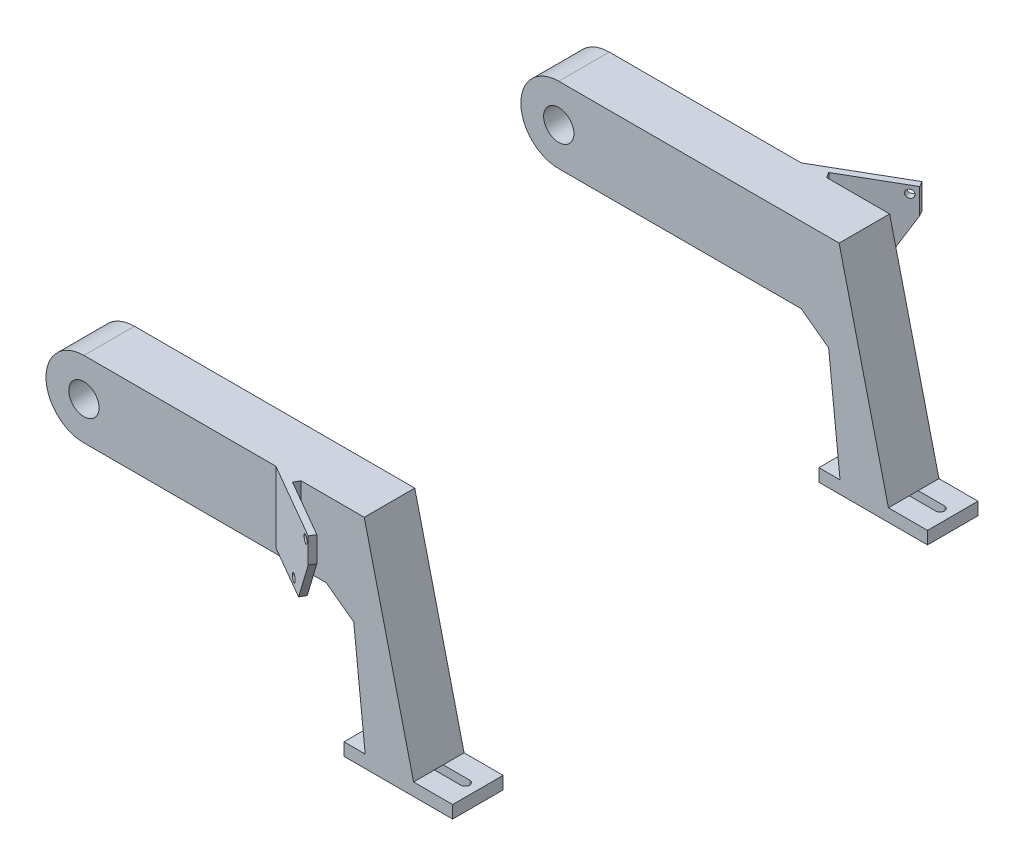
SolidWorks part; units mm, degrees
ref_plane "前视基准面" through (0, 0, 0) normal (0, 0, 1) x (1, 0, 0)
ref_plane "上视基准面" through (0, 0, 0) normal (0, 1, 0) x (1, 0, 0)
ref_plane "右视基准面" through (0, 0, 0) normal (1, 0, 0) x (0, 0, -1)
other "Configuration Table"
sketch "草图1" plane through (0, 0, 0) normal (0, 0, 1) x (1, 0, 0)
  line L1 (3.3481, 16.2319) -> (9.234, -39.7681)
  line L2 (9.234, -39.7681) -> (29.0728, -39.7681)
  line L3 (29.0728, -39.7681) -> (8.3481, 46.2319)
  line L4 (8.3481, 46.2319) -> (-102.6519, 46.2319)
  line L5 (3.3481, 16.2319) -> (-102.6519, 16.2319)
  line L8 (-112.6519, 46.2319) -> (-92.6519, 46.2319) construction
  arc A5 (-102.6519, 46.2319) -> (-102.6519, 16.2319) centre (-102.6519, 31.2319) ccw
  point P7 (-102.6519, 31.2319)
  dimension "D4" = 96
  dimension "D5" = 56
extrude "凸台-拉伸1" add sketch "草图1" along normal blind 20
sketch "草图9" plane through (0, 0, 20) normal (0, 0, 1) x (1, 0, 0)
  circle A0 centre (-102.6519, 31.2319) radius 6
extrude "切除-拉伸5" cut sketch "草图9" against normal through all
sketch "草图15" plane through (0, 0, 20) normal (0, 0, 1) x (1, 0, 0)
  line L0 (4.189, 8.2319) -> (-6.6519, 16.2319)
  line L1 (3.3481, 16.2319) -> (9.234, -39.7681) construction
  line L2 (-102.6519, 16.2319) -> (3.3481, 16.2319) construction
  line L3 (-6.6519, 16.2319) -> (3.3481, 16.2319)
  line L4 (3.3481, 16.2319) -> (4.189, 8.2319)
  dimension "D1" = 10
  dimension "D2" = 8
extrude "凸台-拉伸4" add sketch "草图15" against normal through all
sketch "草图16" plane through (0, 0, 20) normal (0, 0, 1) x (1, 0, 0)
  line L0 (0.3302, -34.7681) -> (0.3302, -49.7681) construction
  line L1 (0.3302, -39.7681) -> (43.3302, -39.7681)
  line L2 (0.3302, -39.7681) -> (0.3302, -34.7681)
  line L3 (0.3302, -34.7681) -> (43.3302, -34.7681)
  line L4 (43.3302, -39.7681) -> (43.3302, -34.7681)
  line L6 (9.234, -39.7681) -> (29.0728, -39.7681) construction
  dimension "D1" = 5
extrude "凸台-拉伸5" add sketch "草图16" against normal through all
sketch "草图17" plane through (0, -34.7681, 0) normal (0, 1, 0) x (1, 0, 0)
  line L0 (4.3302, -10) -> (38.3302, -10) construction
  line L1 (4.3302, -8.25) -> (38.3302, -8.25)
  line L2 (4.3302, -11.75) -> (38.3302, -11.75)
  line L3 (0.3302, -20.5) -> (43.3302, -20.5) construction
  line L6 (43.3302, 0) -> (43.3302, -20) construction
  arc A0 (4.3302, -8.25) -> (4.3302, -11.75) centre (4.3302, -10) ccw
  arc A1 (38.3302, -11.75) -> (38.3302, -8.25) centre (38.3302, -10) ccw
  point P2 (21.3302, -10)
  dimension "D1" = 10.5
  dimension "D2" = 3.5
  dimension "D4" = 5
extrude "切除-拉伸7" cut sketch "草图17" against normal through all
sketch "草图23" plane through (0, 46.2319, 0) normal (0, 1, 0) x (1, 0, 0)
  line L0 (-26.6519, -20) -> (3.659, -37.5)
  line L1 (8.3481, -20) -> (-102.6519, -20) construction
  line L2 (3.659, -37.5) -> (4.909, -35.3349)
  line L3 (4.909, -35.3349) -> (-21.6519, -20)
  line L4 (-21.6519, -20) -> (-26.6519, -20)
  dimension "D1" = 30
  dimension "D2" = 5
  dimension "D3" = 35
  dimension "D4" = 30
extrude "凸台-拉伸6" add sketch "草图23" along direction (0, 1, 0) on the side against the normal up to surface (30 mm away)
sketch "草图25" plane through (0, 46.2319, 0) normal (0, 1, 0) x (1, 0, 0)
  line L0 (-21.6519, -20) -> (-16.6519, -20)
  line L1 (8.3481, -20) -> (-21.6519, -20) construction
  line L2 (-16.6519, -20) -> (-17.9019, -22.1651)
  line L3 (4.909, -35.3349) -> (-21.6519, -20) construction
  line L4 (-17.9019, -22.1651) -> (-21.6519, -20)
  dimension "D1" = 5
extrude "凸台-拉伸7" add sketch "草图25" along direction (0, 1, 0) on the side against the normal up to surface (30 mm away)
sketch "草图26" plane through (-15.3232, 0, 26.5406) normal (-0.5, 0, 0.866) x (0.866, 0, 0.5)
  line L1 (21.9188, 16.2319) -> (-13.0812, 16.2319) construction
  circle A0 centre (19.0303, 43.2289) radius 1.55
  circle A1 centre (6.3303, 21.2319) radius 1.55
  dimension "D4" = 3.1
  dimension "D5" = 3.1
  dimension "D2" = 25.4
  dimension "D3" = 5
extrude "切除-拉伸8" cut sketch "草图26" against normal blind 10
sketch "草图27" plane through (-15.3232, 0, 26.5406) normal (-0.5, 0, 0.866) x (0.866, 0, 0.5)
  line L0 (21.9188, 36.2319) -> (10.3718, 16.2319)
  line L1 (21.9188, 16.2319) -> (21.9188, 46.2319) construction
  line L2 (21.9188, 16.2319) -> (-13.0812, 16.2319) construction
  line L3 (10.3718, 16.2319) -> (21.9188, 16.2319)
  line L4 (21.9188, 16.2319) -> (21.9188, 36.2319)
  dimension "D1" = 30
  dimension "D2" = 20
extrude "切除-拉伸9" cut sketch "草图27" against normal blind 10
sketch "草图28" plane through (0, 16.2319, 0) normal (0, -1, 0) x (1, 0, 0)
  line L0 (-26.6519, 20) -> (-16.6519, 20)
  line L1 (-16.6519, 20) -> (-17.9019, 22.1651)
  line L2 (-17.9019, 22.1651) -> (-5.091, 29.5614)
  line L3 (-5.091, 29.5614) -> (-6.341, 31.7265)
  line L4 (-6.341, 31.7265) -> (-26.6519, 20)
extrude "切除-拉伸10" cut sketch "草图28" against normal blind 2
sketch "草图29" plane through (8.9822, 0, 5.1859) normal (-0.866, 0, -0.5) x (-0.5, 0, 0.866)
  line L4 (28.1464, 16.2319) -> (30.6464, 16.2319)
  line L5 (30.6464, 16.2319) -> (30.6464, 18.2319)
  line L6 (30.6464, 18.2319) -> (28.1464, 18.2319)
  line L7 (28.1464, 18.2319) -> (28.1464, 16.2319)
  line L8 (28.1464, 16.2319) -> (30.6464, 16.2319)
  line L9 (30.6464, 16.2319) -> (30.6464, 18.2319)
  line L10 (30.6464, 18.2319) -> (28.1464, 18.2319)
  line L11 (28.1464, 18.2319) -> (28.1464, 16.2319)
  dimension "D1" = 0
extrude "切除-拉伸11" cut sketch "草图29" against normal blind 2
ref_plane "基准面1" through (0, 0, -84) normal (0, 0, 1) x (1, 0, 0)
mirror "镜向3" about plane through (0, 0, -84) normal (0, 0, 1) of bodies 127
